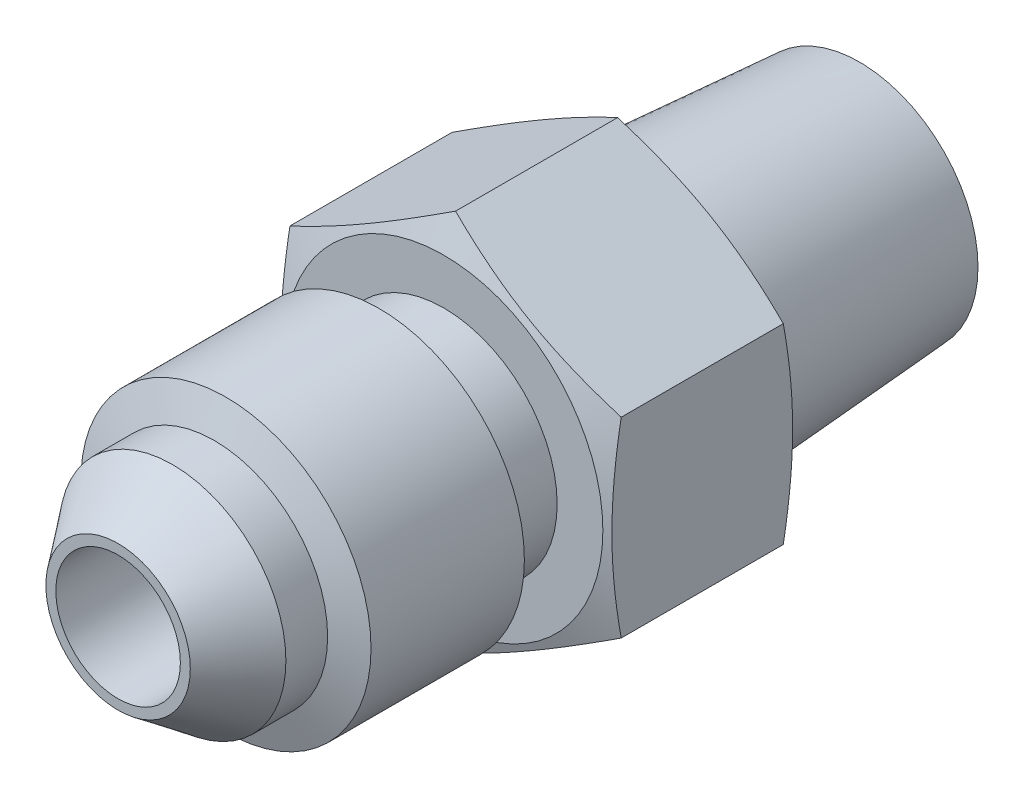
SolidWorks part; units mm, degrees
ref_plane "Front Plane" through (0, 0, 0) normal (0, 0, 1) x (1, 0, 0)
ref_plane "Top Plane" through (0, 0, 0) normal (0, 1, 0) x (1, 0, 0)
ref_plane "Right Plane" through (0, 0, 0) normal (1, 0, 0) x (0, 0, -1)
sketch "Sketch1" plane through (0, 0, 0) normal (1, 0, 0) x (0, 0, -1)
  line L0 (-12.81, 2.3876) -> (-28.4261, 2.3876)
  line L1 (-28.4261, 2.3876) -> (-28.4261, 2.7686)
  line L2 (-28.4261, 2.7686) -> (-26.3363, 4.3434)
  line L3 (-26.3363, 4.3434) -> (-24.7361, 4.3434)
  line L4 (-24.7361, 4.3434) -> (-24.2923, 5.5626)
  line L5 (-24.2923, 5.5626) -> (-18.4132, 5.5626)
  line L6 (-18.4132, 5.5626) -> (-17.9695, 4.3434)
  line L7 (-17.9695, 4.3434) -> (-15.9375, 4.3434)
  line L8 (-15.9375, 4.3434) -> (-15.9375, 6.096)
  line L9 (-15.9375, 6.096) -> (-15.013, 8.636)
  line L10 (-15.013, 8.636) -> (-9.75, 8.636)
  line L11 (-9.75, 8.636) -> (-8.8255, 6.096)
  line L12 (-8.8255, 6.096) -> (-8.8255, 5.1562)
  line L13 (-8.8255, 5.1562) -> (0, 4.5391)
  line L14 (0, 4.5391) -> (0, 2.5781)
  line L15 (-12.81, 2.3876) -> (-12.7, 2.5781)
  line L16 (-12.7, 2.5781) -> (0, 2.5781)
  line L17 (2.002, 0) -> (9.2467, 0) construction
  dimension "D1" = 0.381
  dimension "D2" = 37
  dimension "D3" = 8.6868
  dimension "D4" = 1.2192
  dimension "D5" = 20
  dimension "D6" = 20
  dimension "D7" = 3.69
  dimension "D8" = 6.7666
  dimension "D9" = 2.032
  dimension "D10" = 7.112
  dimension "D11" = 8.8255
  dimension "D12" = 2.54
  dimension "D13" = 12.7
  dimension "D14" = 4.7752
  dimension "D15" = 5.1562
  dimension "D16" = 4
  dimension "D17" = 10.3124
  dimension "D18" = 12.192
  dimension "D19" = 60
  dimension "D20" = 11.1252
revolve "Revolve1" add sketch "Sketch1" angle 360 about L17
sketch "Sketch2" plane through (0, 0, 0) normal (0, 0, 1) x (1, 0, 0)
  line L1 (0, 7.3323) -> (-6.35, 3.6662)
  line L2 (-6.35, 3.6662) -> (-6.35, -3.6662)
  line L3 (-6.35, -3.6662) -> (0, -7.3323)
  line L4 (0, -7.3323) -> (6.35, -3.6662)
  line L5 (6.35, -3.6662) -> (6.35, 3.6662)
  line L6 (6.35, 3.6662) -> (0, 7.3323)
  circle A0 centre (0, 0) radius 6.35 construction
  dimension "D1" = 12.7
extrude "Cut-Extrude1" cut sketch "Sketch2" along normal through all flip side to cut
